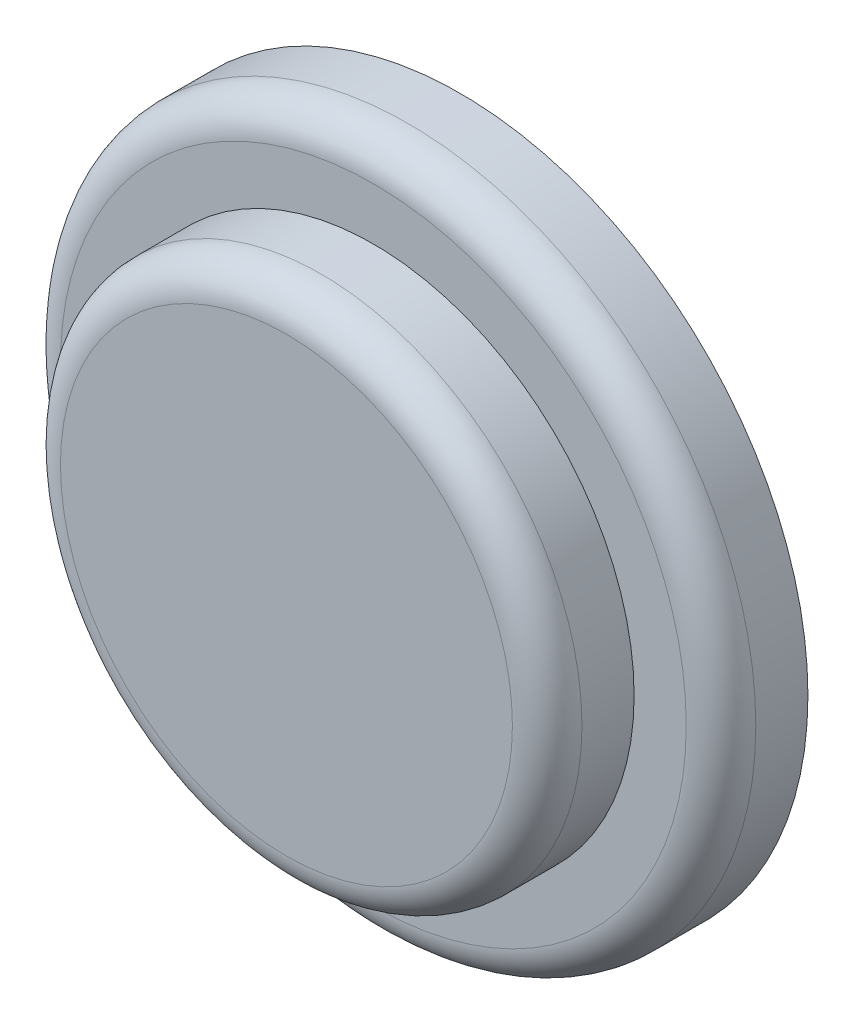
SolidWorks part; units mm, degrees
ref_plane "前视基准面" through (0, 0, 0) normal (0, 0, 1) x (1, 0, 0)
ref_plane "上视基准面" through (0, 0, 0) normal (0, 1, 0) x (1, 0, 0)
ref_plane "右视基准面" through (0, 0, 0) normal (1, 0, 0) x (0, 0, -1)
sketch "草图1" plane through (0, 0, 0) normal (0, 0, 1) x (1, 0, 0)
  circle A0 centre (0, 0) radius 20
extrude "凸台-拉伸1" add sketch "草图1" along normal blind 10
sketch "草图2" plane through (0, 0, 0) normal (0, 0, -1) x (-1, 0, 0)
  circle A0 centre (0, 0) radius 10
extrude "切除-拉伸1" cut sketch "草图2" against normal blind 5
sketch "草图3" plane through (0, 0, 10) normal (0, 0, 1) x (1, 0, 0)
  circle A0 centre (0, 0) radius 20
  circle A1 centre (0, 0) radius 15
extrude "切除-拉伸3" cut sketch "草图3" against normal blind 5 contours A1
fillet "圆角1" radius 2 1 edges at (15, 0, 10)
fillet "圆角2" radius 2 1 edges at (20, 0, 5)
